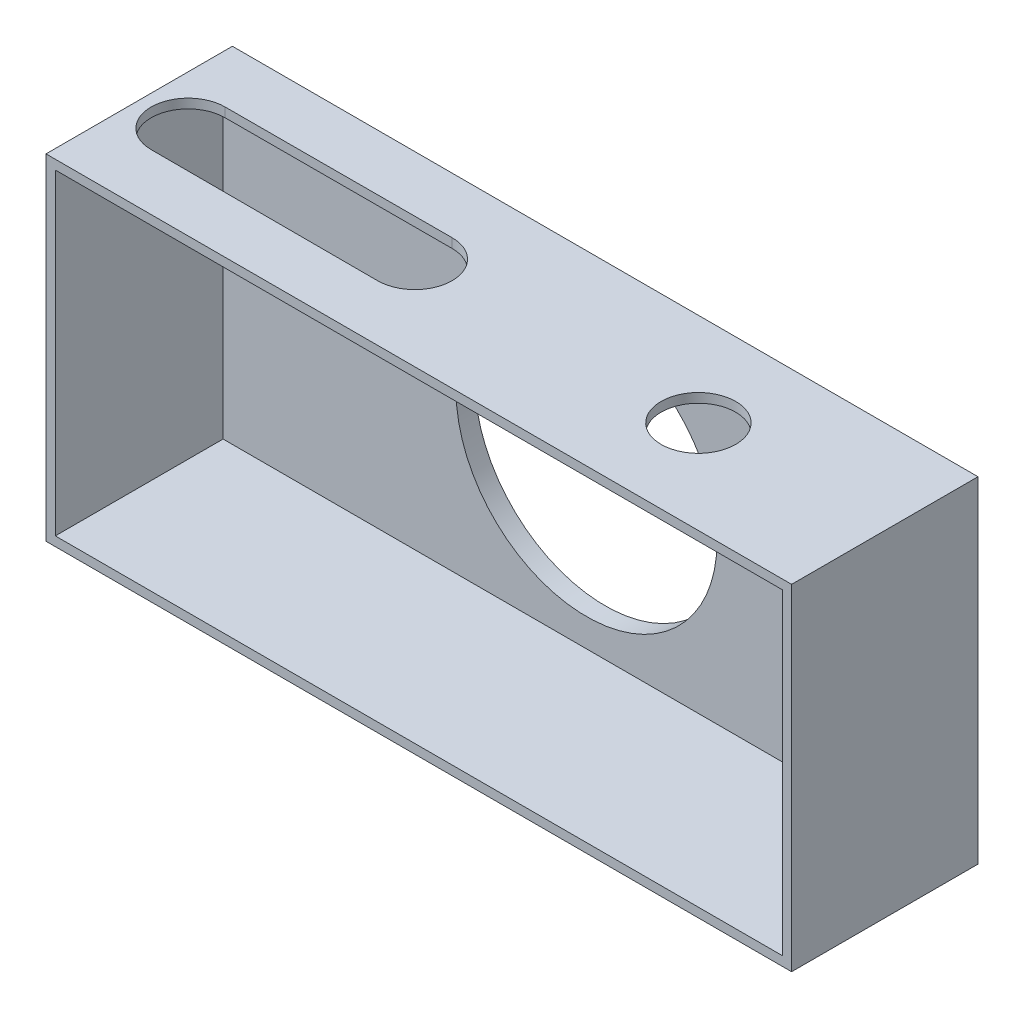
SolidWorks part; units mm, degrees
ref_plane "Front Plane" through (0, 0, 0) normal (0, 0, 1) x (1, 0, 0)
ref_plane "Top Plane" through (0, 0, 0) normal (0, 1, 0) x (1, 0, 0)
ref_plane "Right Plane" through (0, 0, 0) normal (1, 0, 0) x (0, 0, -1)
sketch "Sketch1" plane through (0, 0, 0) normal (0, 0, 1) x (1, 0, 0)
  line L1 (0, 0) -> (-508, 0)
  line L2 (0, 0) -> (0, -228.6)
  line L3 (0, -228.6) -> (-508, -228.6)
  line L4 (-508, 0) -> (-508, -228.6)
  dimension "D1" = 228.6
  dimension "D2" = 508
extrude "Boss-Extrude1" add sketch "Sketch1" along normal blind 127
sketch "Sketch2" plane through (0, 0, 127) normal (0, 0, 1) x (1, 0, 0)
  line L1 (-508, 0) -> (0, -228.6)
  line L2 (-508, -228.6) -> (0, 0)
  line L3 (-6.35, -222.25) -> (-501.65, -222.25)
  line L4 (-6.35, -222.25) -> (-6.35, -6.35)
  line L5 (-6.35, -6.35) -> (-501.65, -6.35)
  line L6 (-501.65, -222.25) -> (-501.65, -6.35)
  line L7 (-6.35, -222.25) -> (-501.65, -6.35) construction
  line L8 (-6.35, -6.35) -> (-501.65, -222.25) construction
  point P0 (-254, -114.3)
  dimension "D1" = 495.3
  dimension "D2" = 215.9
extrude "Cut-Extrude1" cut sketch "Sketch2" against normal blind 114.3 contours L4 L5 L2 L1 L3 | L2 L5 L1 | L6 L3 L2 L1 L5 | L3 L1 L2
sketch "Sketch3" plane through (0, 0, 127) normal (0, 0, 1) x (1, 0, 0)
  line L0 (-501.65, -6.35) -> (-6.35, -222.25) construction
  line L1 (-501.65, -222.25) -> (-6.35, -6.35) construction
  circle A0 centre (-254, -114.3) radius 88.9
extrude "Cut-Extrude2" cut sketch "Sketch3" against normal blind 157.988
sketch "Sketch4" plane through (0, 0, 0) normal (0, 1, 0) x (1, 0, 0)
  line L0 (-508, 0) -> (0, -127) construction
  line L1 (-508, -127) -> (-335.3606, -83.8401) construction
  line L2 (-254, -63.5) -> (-508, -63.5) construction
  line L3 (-508, -127) -> (-508, 0) construction
  line L4 (-254, -63.5) -> (0, -63.5) construction
  line L5 (0, -127) -> (0, 0) construction
  line L6 (-254, 0) -> (0, -127) construction
  line L7 (0, 0) -> (-508, 0) construction
  line L8 (-254, -127) -> (0, 0) construction
  line L9 (0, -127) -> (-508, -127) construction
  line L10 (-508, 0) -> (-254, -127) construction
  line L11 (-254, 0) -> (-508, -127) construction
  line L12 (-474.6655, -38.3148) -> (-320.1685, -38.1126)
  line L13 (-320.1685, -88.8874) -> (-474.6655, -88.6852)
  line L14 (-297.1919, -74.298) -> (0, 0) construction
  circle A0 centre (-127, -63.5) radius 25.4
  arc A1 (-474.6655, -38.3148) -> (-474.6655, -88.6852) centre (-474.6655, -63.5) ccw
  arc A2 (-320.2349, -88.8873) -> (-320.2349, -38.1127) centre (-320.1685, -63.5) ccw
extrude "Cut-Extrude3" cut sketch "Sketch4" against normal blind 157.988 contours L13 A2 L12 A1 | A0
